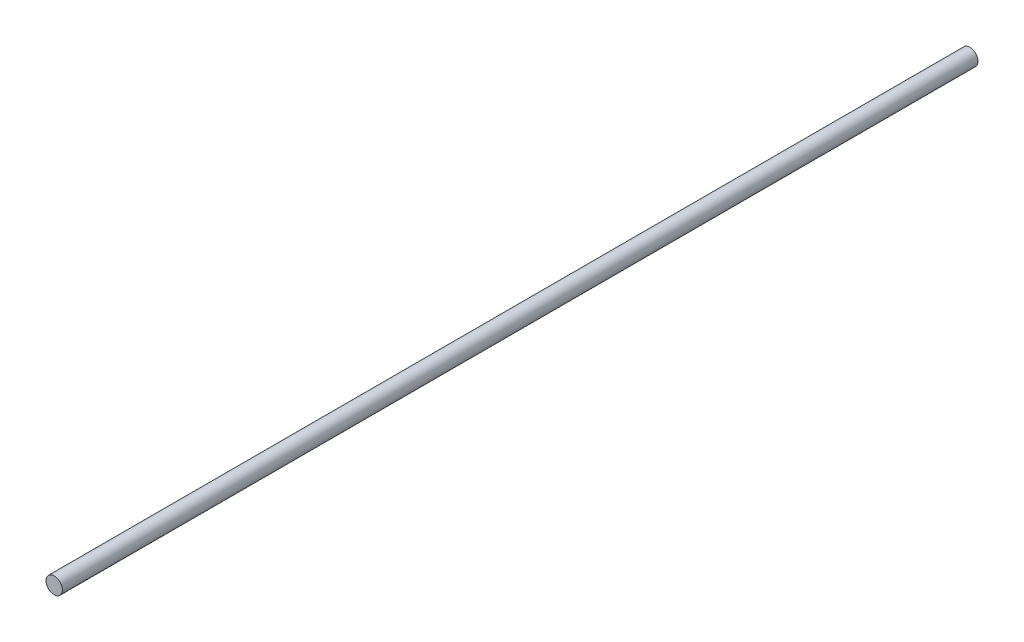
SolidWorks part; units mm, degrees
ref_plane "Front Plane" through (0, 0, 0) normal (0, 0, 1) x (1, 0, 0)
ref_plane "Top Plane" through (0, 0, 0) normal (0, 1, 0) x (1, 0, 0)
ref_plane "Right Plane" through (0, 0, 0) normal (1, 0, 0) x (0, 0, -1)
sketch "Sketch1" plane through (0, 0, 0) normal (0, 0, 1) x (1, 0, 0)
  circle A0 centre (0, 0) radius 1.5875
  dimension "D1" = 3.175
extrude "Boss-Extrude1" add sketch "Sketch1" along normal blind 177.8
